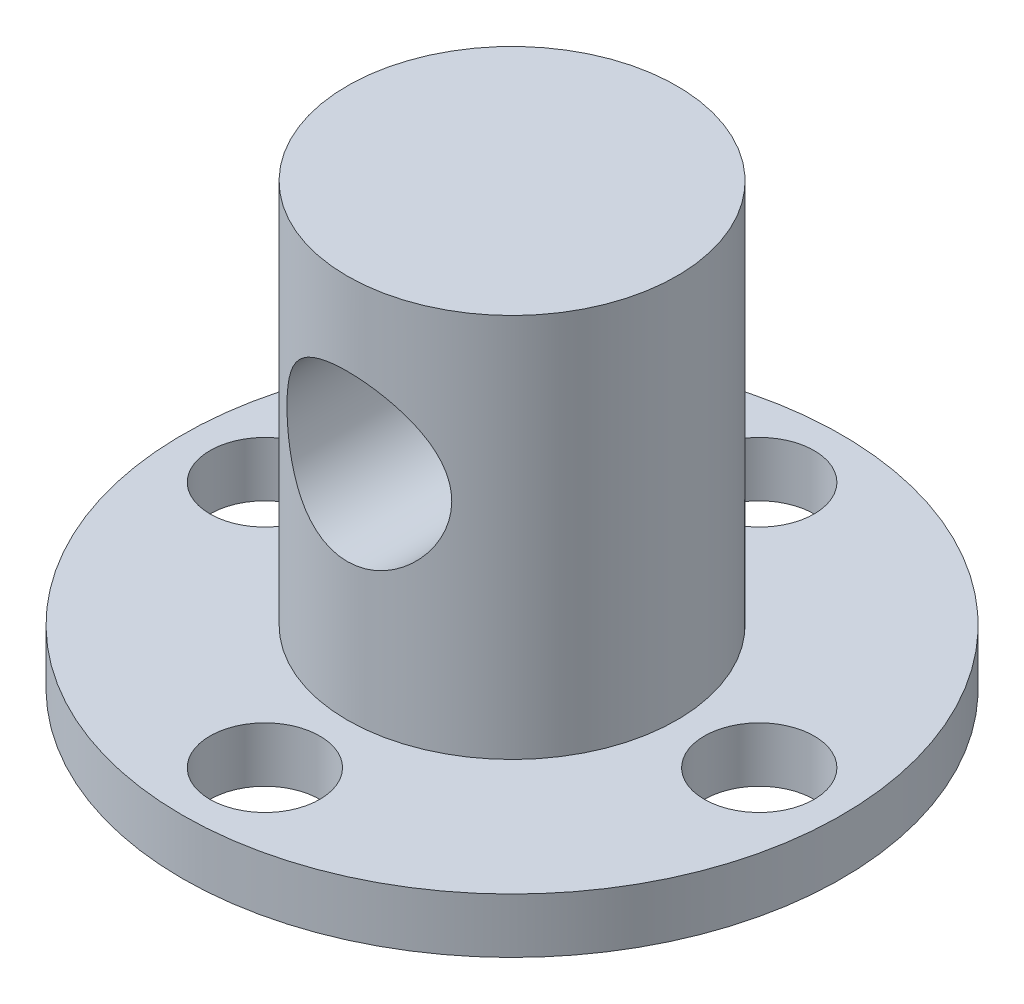
SolidWorks part; units mm, degrees
ref_plane "Front Plane" through (0, 0, 0) normal (0, 0, 1) x (1, 0, 0)
ref_plane "Top Plane" through (0, 0, 0) normal (0, 1, 0) x (1, 0, 0)
ref_plane "Right Plane" through (0, 0, 0) normal (1, 0, 0) x (0, 0, -1)
sketch "Sketch1" plane through (0, 0, 0) normal (0, 1, 0) x (1, 0, 0)
  circle A0 centre (0, 0) radius 30
  dimension "D1" = 60
extrude "Boss-Extrude1" add sketch "Sketch1" along normal blind 5
sketch "Sketch2" plane through (0, 5, 0) normal (0, 1, 0) x (1, 0, 0)
  circle A0 centre (0, 22.5) radius 5
  circle A1 centre (22.5, 0) radius 5
  circle A2 centre (0, -22.5) radius 5
  circle A3 centre (-22.5, 0) radius 5
  point P12 (0, 0)
  dimension "D1" = 10
  dimension "D2" = 22.5
  dimension "D3" = 4
extrude "Cut-Extrude1" cut sketch "Sketch2" against normal blind 5
sketch "Sketch3" plane through (0, 5, 0) normal (0, 1, 0) x (1, 0, 0)
  circle A0 centre (0, 0) radius 15
  dimension "D1" = 30
extrude "Boss-Extrude2" add sketch "Sketch3" along normal blind 35
ref_plane "Plane1" through (0, 0, 15) normal (0, 0, 1) x (1, 0, 0)
sketch "Sketch4" plane through (0, 0, 15) normal (0, 0, 1) x (1, 0, 0)
  line L0 (15, 40) -> (-15, 40) construction
  line L1 (-15, 40) -> (-15, 5) construction
  circle A0 centre (0, 25) radius 7.5
  dimension "D1" = 15
  dimension "D2" = 15
  dimension "D3" = 15
extrude "Cut-Extrude2" cut sketch "Sketch4" against normal through all
